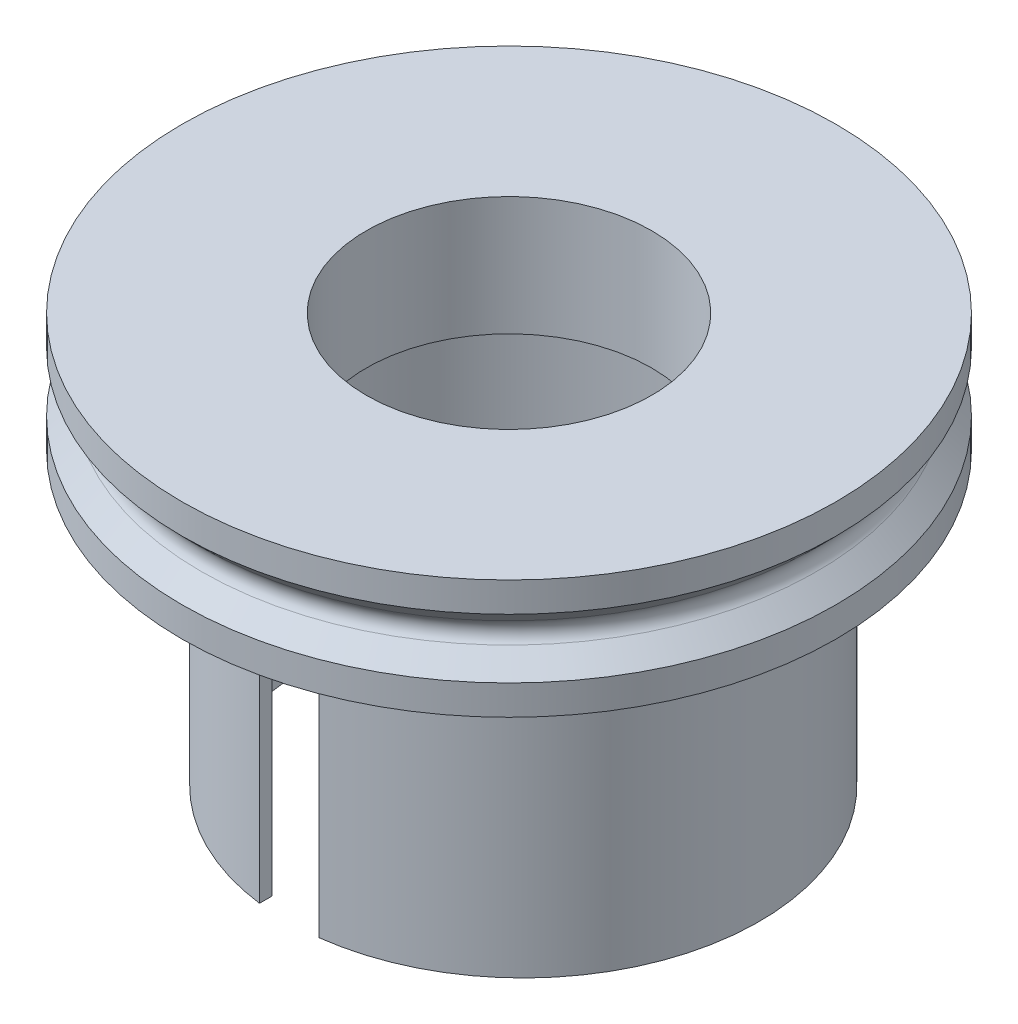
SolidWorks part; units mm, degrees
ref_plane "Front Plane" through (0, 0, 0) normal (0, 0, 1) x (1, 0, 0)
ref_plane "Top Plane" through (0, 0, 0) normal (0, 1, 0) x (1, 0, 0)
ref_plane "Right Plane" through (0, 0, 0) normal (1, 0, 0) x (0, 0, -1)
sketch "Sketch1" plane through (0, 0, 0) normal (0, 1, 0) x (1, 0, 0)
  circle A0 centre (0, 0.762) radius 12.6
  circle A1 centre (0, 0) radius 11.176
  dimension "D1" = 22.352
  dimension "D2" = 25.2
  dimension "D3" = 0.762
extrude "Boss-Extrude1" add sketch "Sketch1" along normal blind 15.875
sketch "Sketch2" plane through (0, 15.875, 0) normal (0, 1, 0) x (1, 0, 0)
  circle A0 centre (0, 0) radius 7.62
  circle A1 centre (0, 0) radius 17.4625
  dimension "D1" = 15.24
  dimension "D2" = 34.925
extrude "Boss-Extrude2" add sketch "Sketch2" along normal blind 6.35
sketch "Sketch3" plane through (0, 0, 0) normal (0, 0, 1) x (1, 0, 0)
  line L0 (0, 22.225) -> (0, 0) construction
  line L1 (17.4625, 22.225) -> (-17.4625, 22.225) construction
  line L2 (-17.4625, 20.6375) -> (-16.4363, 19.6113)
  line L3 (-17.4625, 22.225) -> (-17.4625, 15.875) construction
  line L4 (-16.4363, 18.4887) -> (-17.4625, 17.4625)
  line L5 (-17.4625, 20.6375) -> (-17.4625, 17.4625)
  line L6 (-17.4625, 20.6375) -> (-17.4625, 22.225) construction
  line L7 (-17.4625, 17.4625) -> (-17.4625, 15.875) construction
  arc A0 (-16.4363, 19.6113) -> (-16.4363, 18.4887) centre (-16.9975, 19.05) cw
  dimension "D1" = 0.7937
  dimension "D2" = 45
  dimension "D3" = 3.175
revolve "Cut-Revolve1" cut sketch "Sketch3" angle 360 about L0
sketch "Sketch4" plane through (0, 0, 0) normal (0, -1, 0) x (1, 0, 0)
  line L1 (1.5875, 19.812) -> (-1.5875, 19.812)
  line L2 (1.5875, 19.812) -> (1.5875, 3.864)
  line L3 (1.5875, 3.864) -> (-1.5875, 3.864)
  line L4 (-1.5875, 19.812) -> (-1.5875, 3.864)
  line L5 (1.5875, 19.812) -> (-1.5875, 3.864) construction
  line L6 (1.5875, 3.864) -> (-1.5875, 19.812) construction
  circle A0 centre (0, -0.762) radius 12.6 construction
  circle A1 centre (0, -0.762) radius 12.6 construction
  point P0 (0, 11.838)
  dimension "D1" = 3.175
extrude "Cut-Extrude1" cut sketch "Sketch4" against normal up to surface (15.875 mm away) up to face at (0, 15.875, 11.838)
